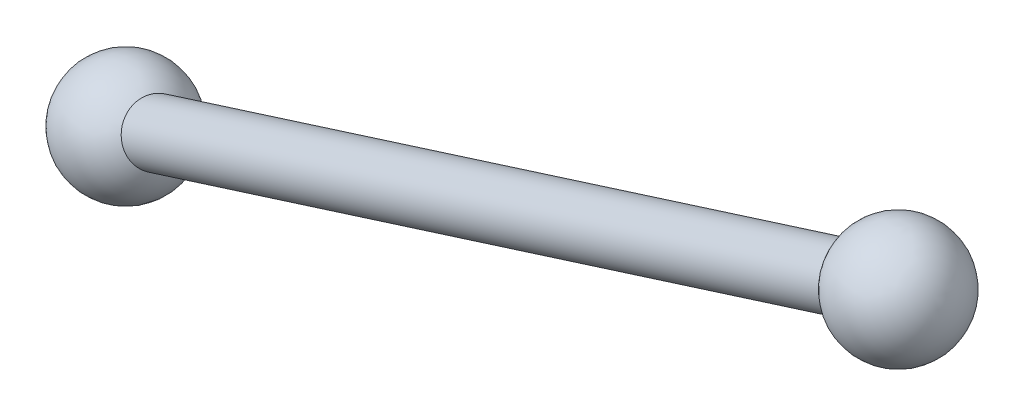
SolidWorks part; units mm, degrees
other "Compression Inner Strut"
ref_plane "Front Plane" through (0, 0, 0) normal (0, 0, 1) x (1, 0, 0)
ref_plane "Top Plane" through (0, 0, 0) normal (0, 1, 0) x (1, 0, 0)
ref_plane "Right Plane" through (0, 0, 0) normal (1, 0, 0) x (0, 0, -1)
sketch3d "Three millimetre strut core sketch datum points"
  point P0 (-26.2917, -73, 0)
  point P1 (-21.3565, -80.6666, -4.1071)
  point P2 (-26.2917, -77.7222, 8.8148)
ref_plane "Three millimetre strut core sketch plane" through (-47.5081, -23.7622, -12.7298) normal (-0.8697, -0.435, -0.233) x (-0.2084, -0.1043, 0.9725)
sketch "Three millimetre strut core sketch" plane through (-47.5081, -23.7622, -12.7298) normal (-0.8697, -0.435, -0.233) x (-0.2084, -0.1043, 0.9725)
  circle A0 centre (13.0902, -53.5275) radius 1.5
extrude "Three millimetre strut core" add sketch "Three millimetre strut core sketch" along normal blind 64.3649 separate body
sketch3d "Ball end 1 axis line"
  line L0 (-26.2917, -73, -10) -> (-26.2917, -73, 10) construction
ref_axis "Ball end 1 axis" through (-26.2917, -73, -10) along (0, 0, 1)
sketch3d "Ball end 1 profile datum points"
  point P0 (-26.2917, -73, 0)
  point P1 (-16.2917, -73, 0)
  point P2 (-26.2917, -73, 10)
ref_plane "Ball end 1 profile plane" through (0, -73, 0) normal (0, -1, 0) x (-1, 0, 0)
sketch "Ball end 1 profile" plane through (0, -73, 0) normal (0, -1, 0) x (-1, 0, 0)
  line L0 (26.2917, -3) -> (26.2917, 3)
  arc A0 (26.2917, 3) -> (26.2917, -3) centre (26.2917, 0) ccw
revolve "Ball end 1" add sketch "Ball end 1 profile" angle 360 about axis through (-26.2917, -73, -10) along (0, 0, 1)
sketch3d "Ball end 2 axis line"
  line L0 (-82.2724, -101, -25) -> (-82.2724, -101, -5) construction
ref_axis "Ball end 2 axis" through (-82.2724, -101, -25) along (0, 0, 1)
sketch3d "Ball end 2 profile datum points"
  point P0 (-82.2724, -101, -15)
  point P1 (-72.2724, -101, -15)
  point P2 (-82.2724, -101, -5)
ref_plane "Ball end 2 profile plane" through (0, -101, 0) normal (0, -1, 0) x (-1, 0, 0)
sketch "Ball end 2 profile" plane through (0, -101, 0) normal (0, -1, 0) x (-1, 0, 0)
  line L0 (82.2724, 12) -> (82.2724, 18)
  arc A0 (82.2724, 18) -> (82.2724, 12) centre (82.2724, 15) ccw
revolve "Ball end 2" add sketch "Ball end 2 profile" angle 360 about axis through (-82.2724, -101, -25) along (0, 0, 1)
